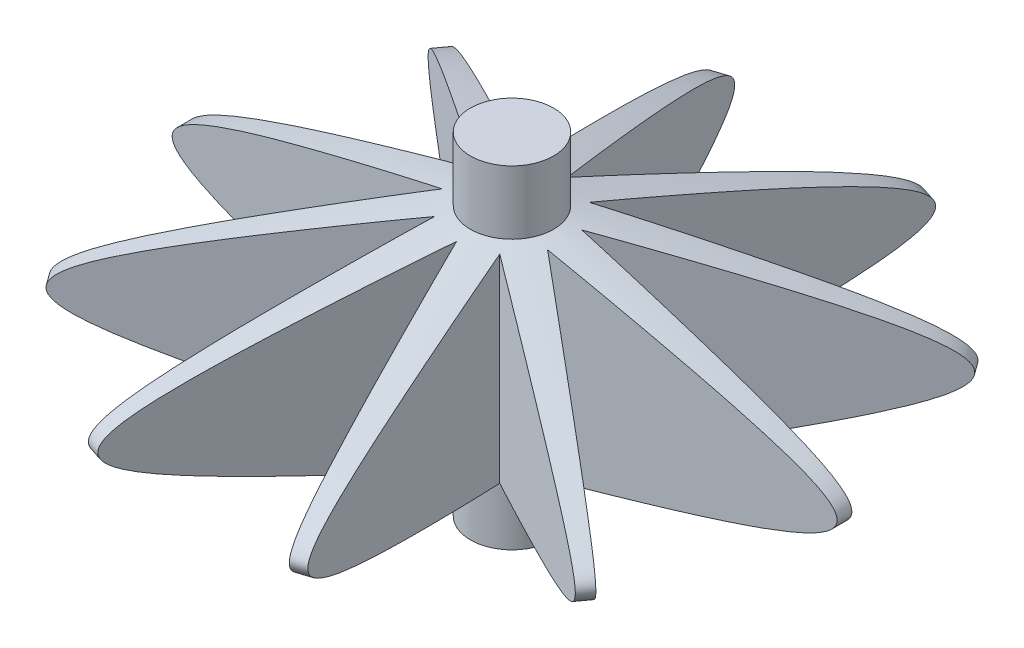
SolidWorks part; units mm, degrees
ref_plane "Front Plane" through (0, 0, 0) normal (0, 0, 1) x (1, 0, 0)
ref_plane "Top Plane" through (0, 0, 0) normal (0, 1, 0) x (1, 0, 0)
ref_plane "Right Plane" through (0, 0, 0) normal (1, 0, 0) x (0, 0, -1)
sketch "Sketch2" plane through (0, 0, 0) normal (0, 0, 1) x (1, 0, 0)
  line L0 (0, 0) -> (9.525, 0)
  line L1 (9.525, 0) -> (9.525, 14.5536)
  line L2 (0, 0) -> (0, 16.6813)
  line L3 (0, 67.4813) -> (0, 76.2)
  line L4 (0, 76.2) -> (9.525, 76.2)
  line L5 (9.525, 76.2) -> (9.525, 61.6464)
  line L6 (0, 67.4813) -> (0, 16.6813)
  line L7 (9.525, 61.6464) -> (9.525, 14.5536) construction
  line L8 (0, 38.1) -> (76.2, 38.1) construction
  line L9 (76.2, 38.1) -> (101.6, 38.1) construction
  arc A0 (9.525, 14.5536) -> (9.525, 61.6464) centre (0, 38.1) ccw construction
  conic Q0 (9.525, 61.6464) -> (9.525, 14.5536) control (101.6, 38.1) rho 0.724138
  dimension "D1" = 25.4
  dimension "D2" = 9.525
  dimension "D3" = 76.2
  dimension "D4" = 25.4
  dimension "D5" = 76.2
revolve "Revolve1" add sketch "Sketch2" angle 360 about L2
sketch "Sketch3" plane through (0, 0, 0) normal (0, 1, 0) x (1, 0, 0)
  line L0 (-27.7345, -88.9) -> (0, -12.7)
  line L1 (0, -12.7) -> (27.7345, -88.9)
  line L2 (27.7345, -88.9) -> (-27.7345, -88.9)
  line L3 (0, 0) -> (0, -12.7) construction
  line L4 (0, -88.9) -> (0, -12.7) construction
  dimension "D1" = 40
  dimension "D2" = 12.7
  dimension "D3" = 76.2
extrude "Cut-Extrude1" cut sketch "Sketch3" along normal through all
pattern_circular "CirPattern2" count 10 over 360 about axis through (0, 0, 0) along (0, 1, 0) of "Cut-Extrude1"
sketch "Sketch4" plane through (0, 0, 0) normal (0, 0, 1) x (1, 0, 0)
  line L0 (9.525, 63.5) -> (50.8, 63.5)
  line L1 (9.525, 61.6464) -> (9.525, 76.2) construction
  line L2 (63.5, 50.8) -> (63.5, 25.4)
  line L3 (50.8, 12.7) -> (9.525, 12.7)
  line L4 (9.525, 12.7) -> (0, 12.7)
  line L5 (0, 12.7) -> (0, 63.5)
  line L6 (0, 63.5) -> (9.525, 63.5)
  line L7 (0, 60.8324) -> (0, 15.3676) construction
  line L8 (0, 60.8324) -> (0, 15.3676) construction
  line L9 (0, 38.1) -> (21.9378, 38.1) construction
  line L10 (0, 0) -> (0, -12.6299) construction
  line L11 (9.525, 0) -> (9.525, 14.5536) construction
  line L12 (21.9378, 38.1) -> (63.5, 38.1) construction
  arc A0 (50.8, 63.5) -> (63.5, 50.8) centre (50.8, 50.8) cw
  arc A1 (63.5, 25.4) -> (50.8, 12.7) centre (50.8, 25.4) cw
  spline S0 degree 3 poles (0, 60.8324) (0.9597, 60.1545) (1.917, 59.4499) (3.8299, 58.0208) (4.7852, 57.2946) (6.6941, 55.8205) (7.6475, 55.0726) (9.5519, 53.5487) (10.5029, 52.7728) (12.4001, 51.1797) (13.3465, 50.3629) (15.2312, 48.6582) (16.1698, 47.7725) (17.5653, 46.3322) (18.0283, 45.8332) (18.7174, 45.0357) (18.9461, 44.7615) (19.4011, 44.1901) (19.6275, 43.8925) (20.0737, 43.2663) (20.294, 42.9377) (20.7246, 42.2293) (20.9353, 41.8508) (21.2371, 41.2079) (21.335, 40.9812) (21.5195, 40.496) (21.6066, 40.2372) (21.7235, 39.8068) (21.7595, 39.658) (21.824, 39.347) (21.8526, 39.1836) (21.8988, 38.8433) (21.9161, 38.6688) (21.937, 38.3098) (21.9403, 38.1241) (21.9318, 37.7623) (21.9202, 37.5831) (21.8839, 37.2314) (21.8598, 37.064) (21.7742, 36.5811) (21.6988, 36.284) (21.5342, 35.7436) (21.4439, 35.4959) (21.2535, 35.0279) (21.1541, 34.8098) (20.8505, 34.1918) (20.6396, 33.824) (20.2093, 33.1334) (19.9896, 32.8116) (19.5446, 32.1971) (19.3191, 31.9044) (18.8656, 31.341) (18.6377, 31.0703) (17.9511, 30.2821) (17.4898, 29.7878) (16.0999, 28.36) (15.1651, 27.4802) (13.2881, 25.786) (12.3456, 24.9737) (10.4563, 23.3889) (9.5094, 22.6169) (7.6135, 21.1006) (6.6643, 20.3563) (4.764, 18.8892) (3.8129, 18.1663) (1.9085, 16.7439) (0.9555, 16.0425) (0, 15.3676) knots 0 0 0 0 0.0625 0.0625 0.125 0.125 0.1875 0.1875 0.25 0.25 0.3125 0.3125 0.375 0.375 0.40625 0.40625 0.421875 0.421875 0.4375 0.4375 0.453125 0.453125 0.46875 0.46875 0.476562 0.476562 0.484375 0.484375 0.488281 0.488281 0.492187 0.492187 0.496094 0.496094 0.5 0.5 0.503906 0.503906 0.507812 0.507812 0.515625 0.515625 0.523437 0.523437 0.53125 0.53125 0.546875 0.546875 0.5625 0.5625 0.578125 0.578125 0.59375 0.59375 0.625 0.625 0.6875 0.6875 0.75 0.75 0.8125 0.8125 0.875 0.875 0.9375 0.9375 1 1 1 1 construction
  dimension "D4" = 12.7
  dimension "D1" = 50.8
  dimension "D3" = 127
